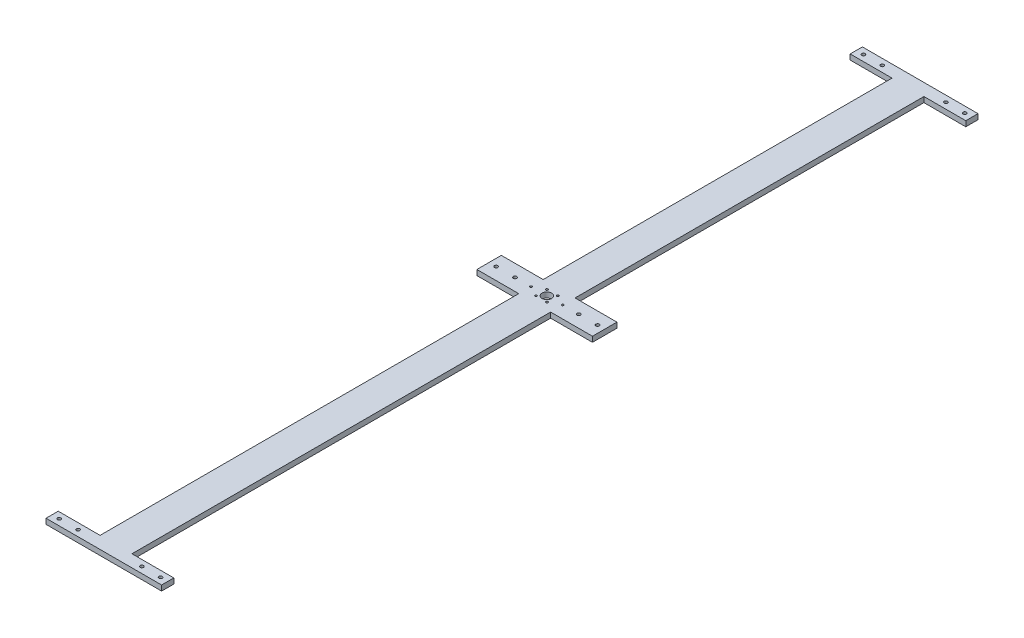
SolidWorks part; units mm, degrees
ref_plane "Front Plane" through (0, 0, 0) normal (0, 0, 1) x (1, 0, 0)
ref_plane "Top Plane" through (0, 0, 0) normal (0, 1, 0) x (1, 0, 0)
ref_plane "Right Plane" through (0, 0, 0) normal (1, 0, 0) x (0, 0, -1)
sketch "Sketch1" plane through (0, 0, 0) normal (0, 1, 0) x (1, 0, 0)
  line L1 (0, 0) -> (108.8, 0)
  line L2 (0, 0) -> (0, 23)
  line L3 (0, 23) -> (108.8, 23)
  line L4 (108.8, 0) -> (108.8, 23)
  dimension "D1" = 108.8
  dimension "D2" = 23
extrude "Mount Base" add sketch "Sketch1" along normal blind 5
sketch "Sketch2" plane through (0, 5, 0) normal (0, 1, 0) x (1, 0, 0)
  line L0 (108.8, 0) -> (108.8, 23) construction
  line L1 (0, 0) -> (108.8, 0) construction
  circle A0 centre (59.55, 16.6) radius 1
  circle A1 centre (59.55, 6.4) radius 1
  circle A2 centre (49.25, 6.4) radius 1
  circle A3 centre (49.25, 16.6) radius 1
  circle A4 centre (69.31, 11.5) radius 1
  circle A5 centre (39.49, 11.5) radius 1
  circle A6 centre (54.4, 11.5) radius 4.5
  point P16 (108.8, 11.5)
  point P19 (54.4, 0)
  dimension "D4" = 9
  dimension "D1" = 2
  dimension "D3" = 10.3
  dimension "D5" = 5.15
  dimension "D6" = 5.1
  dimension "D2" = 10.2
  dimension "D7" = 14.91
  dimension "D8" = 14.91
extrude "Bracket Screw Holes" cut sketch "Sketch2" against normal up to surface (5 mm away) up to face at (54.4, 0, -11.5)
sketch "Sketch3" plane through (0, 5, 0) normal (0, 1, 0) x (1, 0, 0)
  line L0 (0, 23) -> (0, 0) construction
  circle A0 centre (6.7, 11.5) radius 1.5875
  circle A1 centre (24.4, 11.5) radius 1.5875
  circle A2 centre (84.4, 11.5) radius 1.5875
  circle A3 centre (102.1, 11.5) radius 1.5875
  circle A4 centre (54.4, 11.5) radius 4.5 construction
  point P13 (0, 11.5)
  dimension "D1" = 3.175
  dimension "D2" = 17.7
  dimension "D3" = 17.7
  dimension "D4" = 30
  dimension "D5" = 30
extrude "Antenna Screw Holes" cut sketch "Sketch3" against normal up to surface (5 mm away) up to face at (59.55, 0, -7.4)
sketch "Sketch6" plane through (0, 0, -23) normal (0, 0, -1) x (-1, 0, 0)
  line L0 (-108.8, 5) -> (0, 5) construction
  line L1 (-39.4, 5) -> (-69.4, 5)
  line L2 (-39.4, 5) -> (-39.4, 0)
  line L3 (-39.4, 0) -> (-69.4, 0)
  line L4 (-69.4, 5) -> (-69.4, 0)
  line L5 (-108.8, 0) -> (0, 0) construction
  point P9 (-54.4, 5)
  point P10 (-54.4, 5)
  dimension "D1" = 30
extrude "Director Extension" add sketch "Sketch6" along normal blind 328.35
sketch "Sketch7" plane through (0, 0, -351.35) normal (0, 0, -1) x (-1, 0, 0)
  line L0 (-108.8, 5) -> (-108.8, 0) construction
  line L1 (-108.8, 5) -> (0, 5)
  line L2 (-108.8, 5) -> (-108.8, 0)
  line L3 (-108.8, 0) -> (0, 0)
  line L4 (0, 5) -> (0, 0)
extrude "Director Mount" add sketch "Sketch7" along normal blind 11.5
sketch "Sketch10" plane through (0, 0, 0) normal (0, 0, 1) x (1, 0, 0)
  line L0 (0, 5) -> (108.8, 5) construction
  line L1 (39.4, 5) -> (69.4, 5)
  line L2 (39.4, 5) -> (39.4, 0)
  line L3 (39.4, 0) -> (69.4, 0)
  line L4 (69.4, 5) -> (69.4, 0)
  line L5 (0, 0) -> (108.8, 0) construction
extrude "Reflector Extension" add sketch "Sketch10" along normal blind 394.02
sketch "Sketch11" plane through (0, 0, 394.02) normal (0, 0, 1) x (1, 0, 0)
  line L0 (108.8, 5) -> (108.8, 0) construction
  line L1 (0, 5) -> (108.8, 5)
  line L2 (0, 5) -> (0, 0)
  line L3 (0, 0) -> (108.8, 0)
  line L4 (108.8, 5) -> (108.8, 0)
extrude "Reflector Mount" add sketch "Sketch11" along normal blind 11.5
pattern_linear "LPattern1" count 2 spacing 411.27 along (0, 0, 1) count 2 spacing 345.6 along (0, 0, -1) of "Antenna Screw Holes"
equation "\"D8@Sketch2\"=\"D7@Sketch2\""
equation "\"D7@Sketch2\"=8.76+\"D3@Sketch2\"/2 + \"D1@Sketch2\"/2"
equation "\"D6@Sketch2\"=\"D2@Sketch2\"/2"
equation "\"D5@Sketch2\"=\"D3@Sketch2\"/2"
equation "\"D3@Sketch3\"=\"D2@Sketch3\""
equation "\"D5@Sketch3\"=\"D4@Sketch3\""
equation "\"MountWidth\"=23"
equation "\"D2@Sketch1\"=\"MountWidth\""
equation "\"D1@Director Mount\" = \"MountWidth\" / 2"
equation "\"ExtensionLength\"=100"
equation "\"D1@Director Extension\"=\"lambda\"*0.15"
equation "\"D1@Reflector Extension\"=\"lambda\"*0.18"
equation "\"D1@Reflector Mount\" = \"MountWidth\" / 2"
equation "\"D4@LPattern1\"=\"lambda\"*0.15+\"MountWidth\"*3/4"
equation "\"D3@LPattern1\"=\"lambda\"*0.18+\"MountWidth\"*3/4"
equation "\"lambda\"= 218.9cm"
